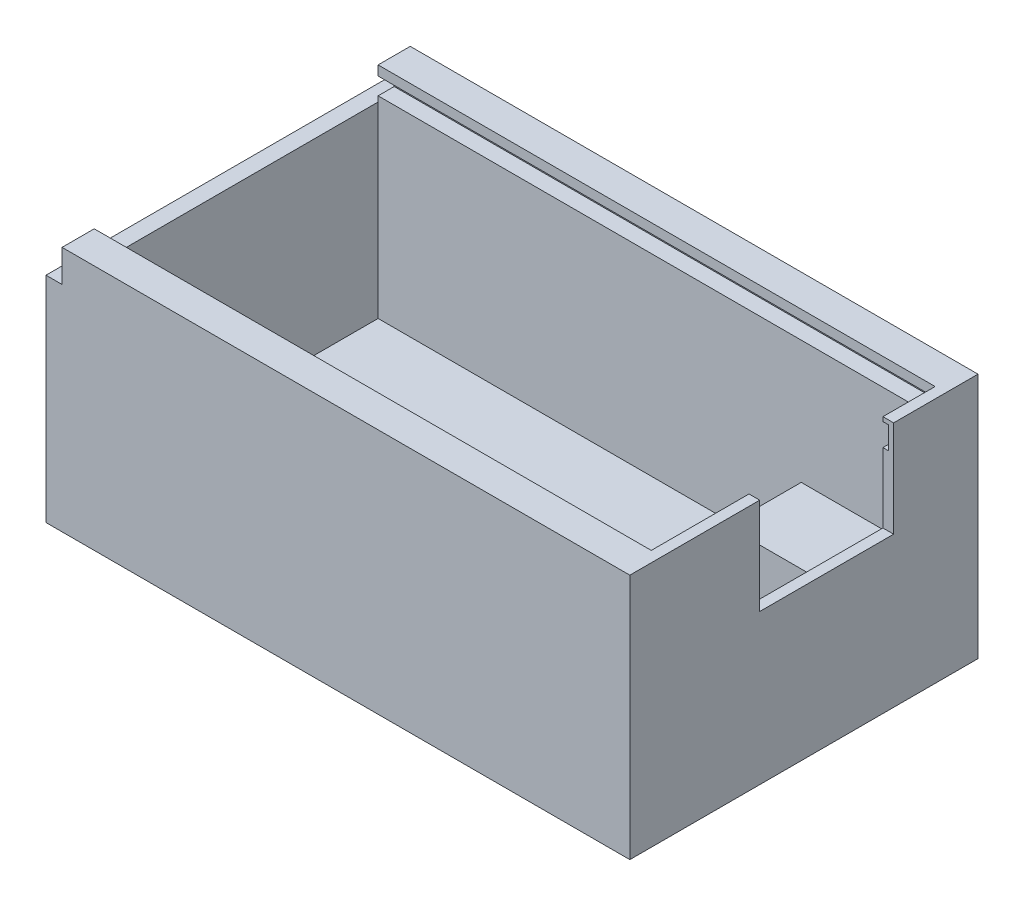
SolidWorks part; units mm, degrees
ref_plane "Front Plane" through (0, 0, 0) normal (0, 0, 1) x (1, 0, 0)
ref_plane "Top Plane" through (0, 0, 0) normal (0, 1, 0) x (1, 0, 0)
ref_plane "Right Plane" through (0, 0, 0) normal (1, 0, 0) x (0, 0, -1)
sketch "Sketch2" plane through (0, 0, 0) normal (0, 1, 0) x (1, 0, 0)
  line L1 (0, 0) -> (104, 0)
  line L2 (0, 0) -> (0, 53)
  line L3 (0, 53) -> (104, 53)
  line L4 (104, 0) -> (104, 53)
  line L9 (-3, -6) -> (106, -6)
  line L10 (-3, -6) -> (-3, 59)
  line L11 (-3, 59) -> (106, 59)
  line L12 (106, -6) -> (106, 59)
  line L13 (104, 53) -> (79, 53)
  line L14 (104, 53) -> (104, 39)
  line L15 (104, 39) -> (79, 39)
  line L16 (79, 53) -> (79, 39)
  line L17 (79, 14) -> (104, 14)
  line L18 (79, 14) -> (79, 0)
  line L19 (79, 0) -> (104, 0)
  line L20 (104, 14) -> (104, 0)
  dimension "D1" = 104
  dimension "D2" = 53
  dimension "D3" = 2
  dimension "D4" = 3
  dimension "D5" = 6
  dimension "D6" = 6
  dimension "D7" = 25
  dimension "D8" = 25
extrude "Boss-Extrude1" add sketch "Sketch2" along normal blind 41 contours L9 L12 L11 L10 L4 L1 L2 L3 | L3 L16 L15 L4 | L17 L18 L1 L4
sketch "Sketch3" plane through (0, 0, 0) normal (0, -1, 0) x (1, 0, 0)
  line L1 (-3, 6) -> (106, 6)
  line L2 (-3, 6) -> (-3, -59)
  line L3 (-3, -59) -> (106, -59)
  line L4 (106, 6) -> (106, -59)
extrude "Boss-Extrude2" add sketch "Sketch3" along normal blind 5
sketch "Sketch4" plane through (-3, 0, 0) normal (-1, 0, 0) x (0, 0, 1)
  line L0 (6, 41) -> (6, -5) construction
  line L1 (-59, 41) -> (6, 41)
  line L2 (-59, 41) -> (-59, 35)
  line L3 (-59, 35) -> (6, 35)
  line L4 (6, 41) -> (6, 35)
  dimension "D1" = 6
extrude "Cut-Extrude1" cut sketch "Sketch4" against normal blind 3 contours L1 L4 L3 L2
sketch "Sketch5" plane through (106, 0, 0) normal (1, 0, 0) x (0, 0, -1)
  line L0 (59, 41) -> (59, -5) construction
  line L1 (-6, -5) -> (59, -5) construction
  line L2 (-6, -5) -> (-6, 0) construction
  line L3 (-6, 0) -> (59, 0) construction
  line L4 (59, -5) -> (59, 0) construction
  line L5 (-6, 41) -> (59, 41) construction
  line L6 (18.25, 41) -> (34.75, 41) construction
  line L7 (18.25, 41) -> (18.25, 23) construction
  line L8 (18.25, 23) -> (34.75, 23) construction
  line L9 (34.75, 41) -> (34.75, 23) construction
  line L11 (18.25, 23) -> (43.25, 23)
  line L12 (18.25, 23) -> (18.25, 41)
  line L13 (18.25, 41) -> (43.25, 41)
  line L14 (43.25, 23) -> (43.25, 41)
  point P13 (0, 0)
  dimension "D1" = 5
  dimension "D2" = 16.5
  dimension "D3" = 24.25
  dimension "D4" = 18
  dimension "D5" = 25
extrude "Cut-Extrude2" cut sketch "Sketch5" against normal blind 10
sketch "Sketch6" plane through (79, 0, 0) normal (-1, 0, 0) x (0, 0, 1)
  line L0 (-53, 41) -> (-53, 0) construction
  line L1 (-53, 13) -> (0, 13)
  line L2 (-53, 13) -> (-53, 41)
  line L3 (-53, 41) -> (0, 41)
  line L4 (0, 13) -> (0, 41)
  line L5 (-43.25, 13) -> (-34.75, 13) construction
  line L6 (-53, 0) -> (-39, 0) construction
  dimension "D1" = 13
extrude "Cut-Extrude3" cut sketch "Sketch6" against normal up to surface (25 mm away) up to face at (104, 21.3333, -23.75)
sketch "Sketch7" plane through (0, 0, 0) normal (-1, 0, 0) x (0, 0, 1)
  line L0 (-53, 13) -> (-53, 41) construction
  line L1 (-53, 39.2) -> (-56, 39.2)
  line L2 (-53, 39.2) -> (-53, 36)
  line L3 (-53, 36) -> (-56, 36)
  line L4 (-56, 39.2) -> (-56, 36)
  line L5 (-59, 35) -> (-53, 35) construction
  line L6 (-26.5, 35) -> (-26.5, 48.4877) construction
  line L12 (-59, 35) -> (6, 35) construction
  line L13 (3, 39.2) -> (3, 36)
  line L14 (0, 36) -> (3, 36)
  line L15 (0, 39.2) -> (0, 36)
  line L16 (0, 39.2) -> (3, 39.2)
  dimension "D1" = 3
  dimension "D2" = 3.2
  dimension "D3" = 1
extrude "Cut-Extrude4" cut sketch "Sketch7" along direction (-1, 0, 0) on the side against the normal offset from surface (105.25 mm away) 1.25
sketch "Sketch8" plane through (104, 0, 0) normal (-1, 0, 0) x (0, 0, 1)
  line L1 (-53, 40.2) -> (0, 40.2)
  line L2 (-53, 40.2) -> (-53, 36)
  line L3 (-53, 36) -> (0, 36)
  line L4 (0, 40.2) -> (0, 36)
  line L5 (0, 36) -> (0, 13) construction
  line L6 (-53, 39.2) -> (-53, 41) construction
  line L8 (-53, 39.2) -> (-48.5602, 39.2) construction
  line L9 (-53, 36) -> (-47.1891, 36) construction
  dimension "D2" = 1
extrude "Cut-Extrude5" cut sketch "Sketch8" against normal blind 1
equation "\"d1\"=11.9805"
equation "\"D1@Sketch2\"=\"D7@Sketch2\"+(86-7)"
